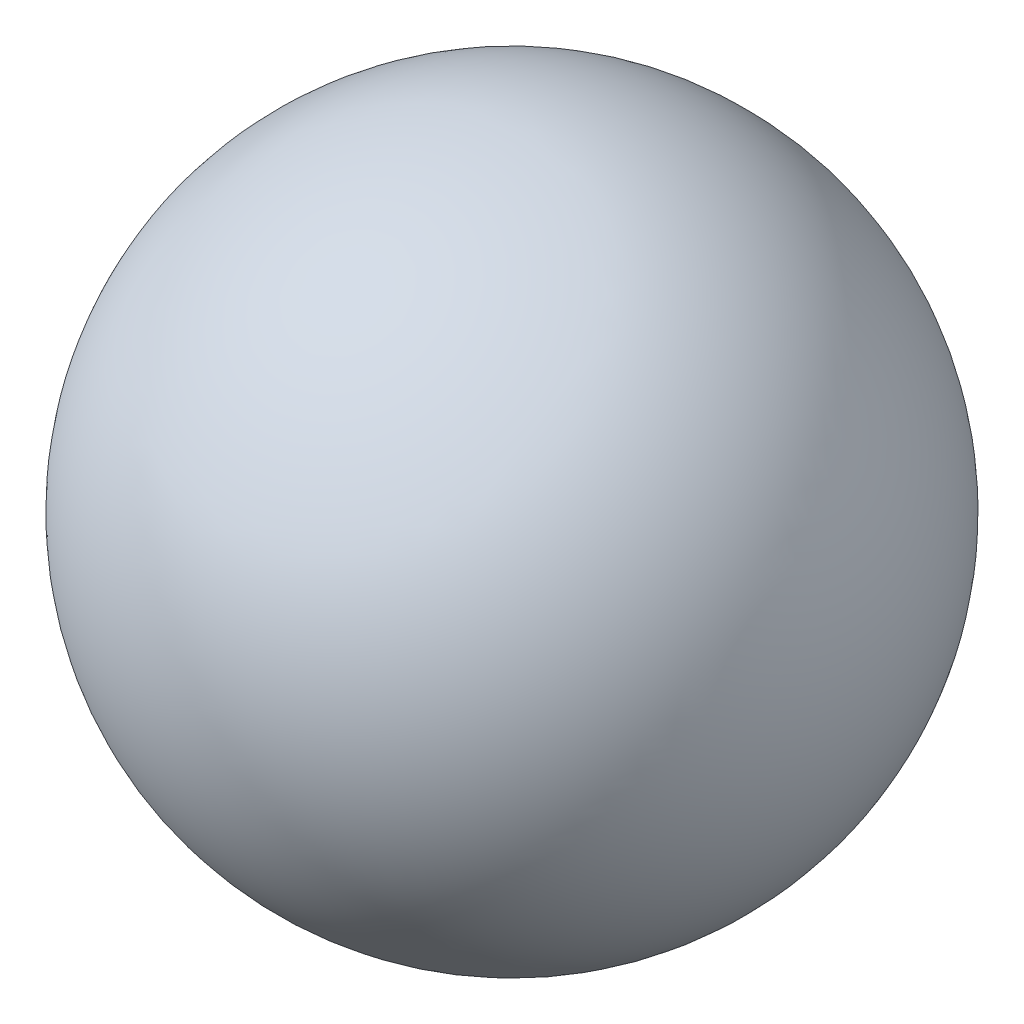
SolidWorks part; units mm, degrees
ref_plane "Front Plane" through (0, 0, 0) normal (0, 0, 1) x (1, 0, 0)
ref_plane "Top Plane" through (0, 0, 0) normal (0, 1, 0) x (1, 0, 0)
ref_plane "Right Plane" through (0, 0, 0) normal (1, 0, 0) x (0, 0, -1)
sketch "Sketch1" plane through (0, 0, 0) normal (0, 0, 1) x (1, 0, 0)
  line L0 (-19.05, 0) -> (19.05, 0)
  arc A0 (-19.05, 0) -> (19.05, 0) centre (0, 0) cw
  point P4 (0, 0)
  point P6 (0, 0)
  dimension "D1" = 38.1
revolve "Revolve1" add sketch "Sketch1" angle 360 about L0
